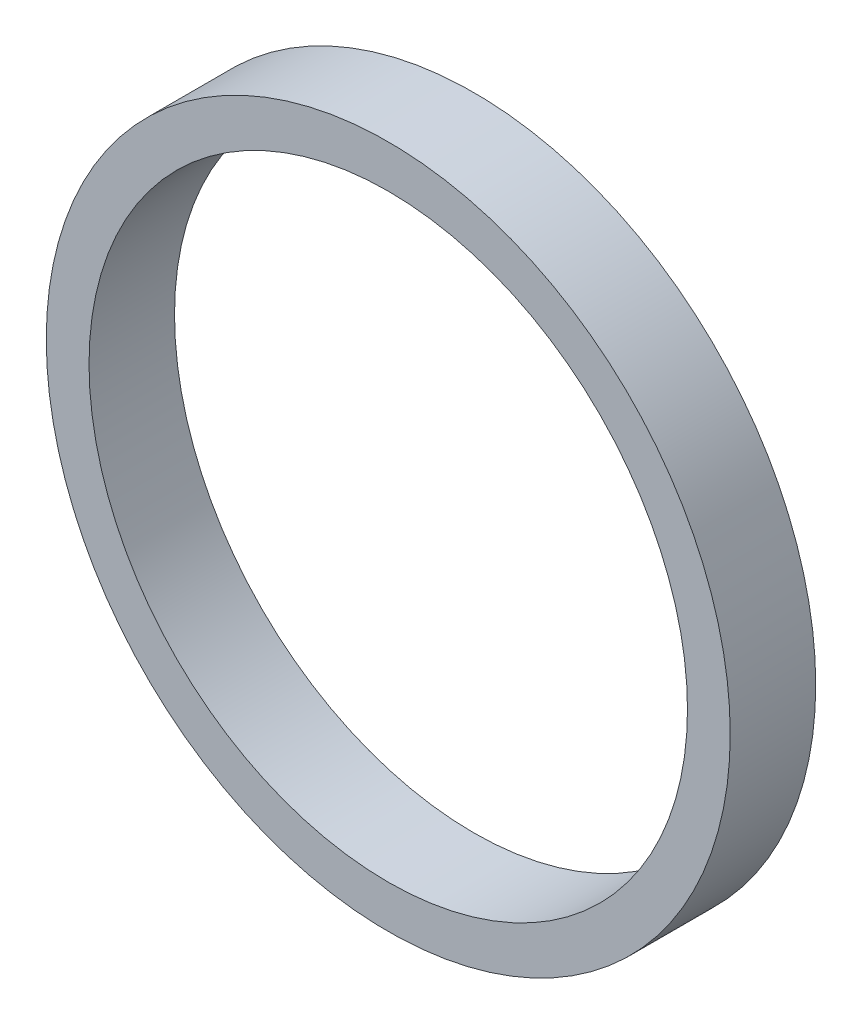
SolidWorks part; units mm, degrees
ref_plane "Front Plane" through (0, 0, 0) normal (0, 0, 1) x (1, 0, 0)
ref_plane "Top Plane" through (0, 0, 0) normal (0, 1, 0) x (1, 0, 0)
ref_plane "Right Plane" through (0, 0, 0) normal (1, 0, 0) x (0, 0, -1)
sketch "Sketch2" plane through (0, 0, 0) normal (0, 0, 1) x (1, 0, 0)
  circle A0 centre (0, 0) radius 40
  dimension "D1" = 80
extrude "Boss-Extrude1" add sketch "Sketch2" along normal mid plane 10
sketch "Sketch3" plane through (0, 0, 5) normal (0, 0, 1) x (1, 0, 0)
  circle A0 centre (0, 0) radius 35
  dimension "D1" = 70
extrude "Cut-Extrude1" cut sketch "Sketch3" against normal through all contours A0
